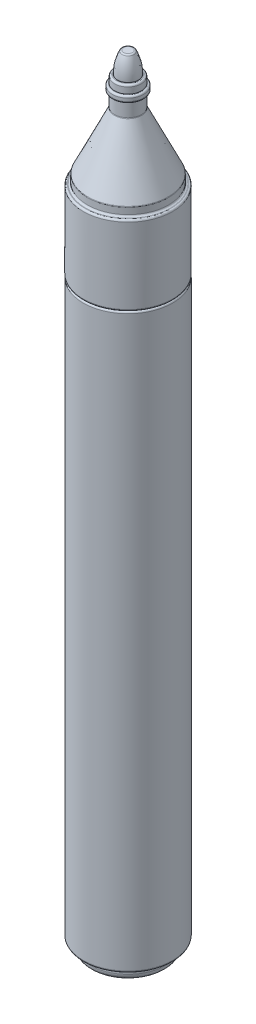
SolidWorks part; units mm, degrees
ref_plane "Front" through (0, 0, 0) normal (0, 0, 1) x (1, 0, 0)
ref_plane "Top" through (0, 0, 0) normal (0, 1, 0) x (1, 0, 0)
ref_plane "Right" through (0, 0, 0) normal (1, 0, 0) x (0, 0, -1)
sketch "Sketch1" plane through (0, 0, 0) normal (0, 1, 0) x (1, 0, 0)
  circle A0 centre (0, 0) radius 7.5
  dimension "D1" = 15
extrude "Boss-Extrude1" add sketch "Sketch1" along normal blind 96
fillet "Fillet1" radius 0.3 2 edges at (0, 0, 7.5) (0, 96, 7.5)
sketch "Sketch2" plane through (0, 0, 0) normal (0, -1, 0) x (-1, 0, 0)
  circle A0 centre (0, 0) radius 6.3495
extrude "Boss-Extrude2" add sketch "Sketch2" along normal blind 2
sketch "Sketch3" plane through (0, 0, 0) normal (0, 0, 1) x (1, 0, 0)
  line L0 (0, 96) -> (0, 128.677)
  line L1 (0, 96) -> (7.5, 96)
  line L2 (7.2, 96) -> (-7.2, 96) construction
  line L3 (7.5, 96) -> (7.5, 109.2867)
  line L4 (7.5, 109.2867) -> (6.7944, 109.2867)
  line L5 (6.7944, 109.2867) -> (6.7944, 110.7154)
  line L6 (6.7944, 110.7154) -> (2.2352, 120.3563)
  line L8 (2.2352, 122.7542) -> (2.6377, 122.7542)
  line L9 (2.6377, 122.7542) -> (2.6377, 123.8592)
  line L10 (2.6377, 123.8592) -> (2.2352, 123.8592)
  line L11 (2.2352, 123.8592) -> (2.2352, 125.1877)
  line L12 (2.2352, 125.1877) -> (1.7722, 125.1877)
  line L13 (0, 128.677) -> (0.9102, 128.677)
  line L14 (2.2352, 122.7542) -> (2.2352, 120.3563)
  line L15 (1.7117, 125.1877) -> (1.7117, 124.5276)
  line L16 (1.7117, 124.5276) -> (1.7722, 124.5276)
  line L17 (1.7722, 124.5276) -> (1.7722, 125.1877)
  spline S0 degree 3 poles (0.9102, 128.677) (1.4898, 127.6515) (1.7569, 126.4885) (1.7117, 125.1877) knots 0.29863 0.29863 0.29863 0.29863 1 1 1 1
revolve "Revolve1" add sketch "Sketch3" angle 360 about L0
fillet "Fillet2" radius 0.3 1 edges at (0, 96, -7.5)
fillet "Fillet3" radius 0.3 8 edges at (0, 109.2867, -7.5) (0, 109.2867, -6.7944) (0, 110.7154, -6.7944) (0, 120.3563, -2.2352) (0, 122.7542, -2.6377) (0, 123.8592, -2.6377) (0, 128.677, -0.9102) (0, 125.1877, -2.2352)
fillet "Fillet4" radius 1 1 edges at (0, -2, -6.3495)
